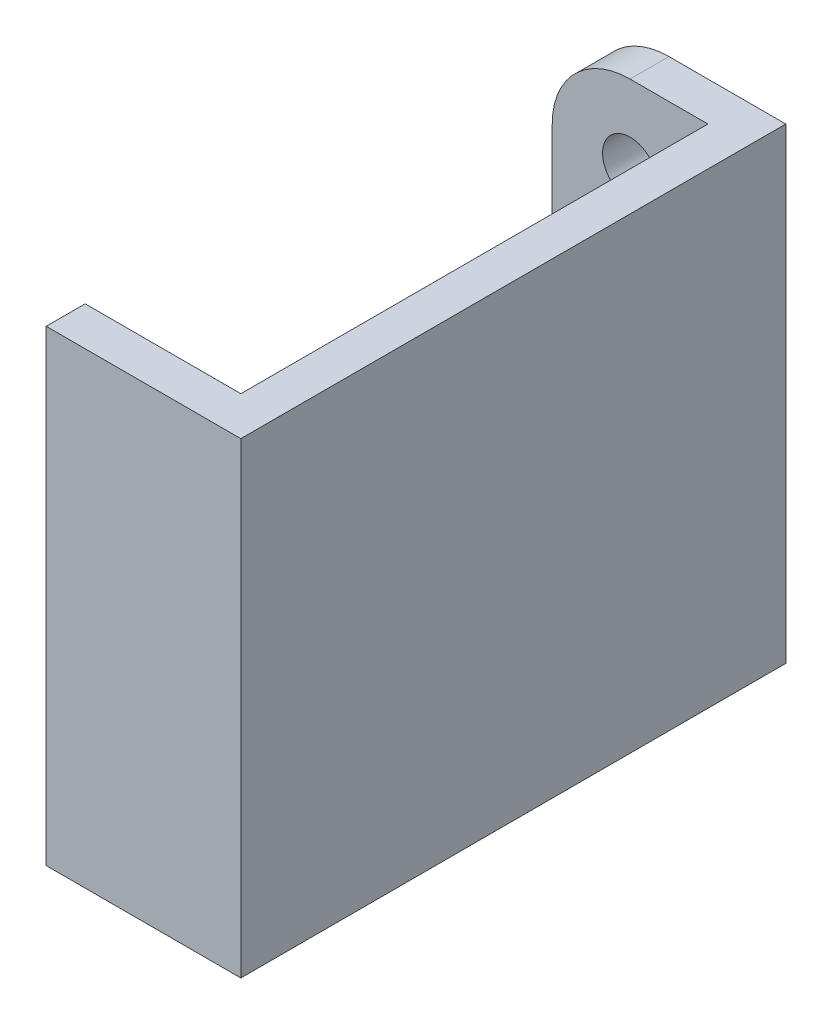
SolidWorks part; units mm, degrees
material "PET"
ref_plane "Front Plane" through (0, 0, 0) normal (0, 0, 1) x (1, 0, 0)
ref_plane "Top Plane" through (0, 0, 0) normal (0, 1, 0) x (1, 0, 0)
ref_plane "Right Plane" through (0, 0, 0) normal (1, 0, 0) x (0, 0, -1)
sketch "Sketch1" plane through (0, 0, 0) normal (0, 0, 1) x (1, 0, 0)
  line L1 (-7.9375, 19.05) -> (7.9375, 19.05)
  line L2 (-7.9375, 19.05) -> (-7.9375, -19.05)
  line L3 (-7.9375, -19.05) -> (7.9375, -19.05)
  line L4 (7.9375, 19.05) -> (7.9375, -19.05)
  line L5 (-7.9375, 19.05) -> (7.9375, -19.05) construction
  line L6 (-7.9375, -19.05) -> (7.9375, 19.05) construction
  point P0 (0, 0)
  dimension "D1" = 38.1
  dimension "D2" = 15.875
extrude "Boss-Extrude1" add sketch "Sketch1" against normal blind 44.45
shell "Shell1" thickness 3.175
sketch "Sketch2" plane through (0, 0, -3.175) normal (0, 0, 1) x (1, 0, 0)
  line L0 (7.9375, 19.05) -> (-7.9375, 19.05) construction
  line L1 (-7.9375, 19.05) -> (-7.9375, -19.05) construction
  circle A0 centre (-1.5875, -6.35) radius 2.2479
  circle A1 centre (-1.5875, 12.7) radius 2.2479
  dimension "D1" = 4.4958
  dimension "D2" = 19.05
  dimension "D3" = 6.35
  dimension "D4" = 6.35
extrude "Cut-Extrude1" cut sketch "Sketch2" against normal up to next
fillet "Fillet2" radius 6.35 1 edges at (-7.9375, 19.05, -42.8625)
